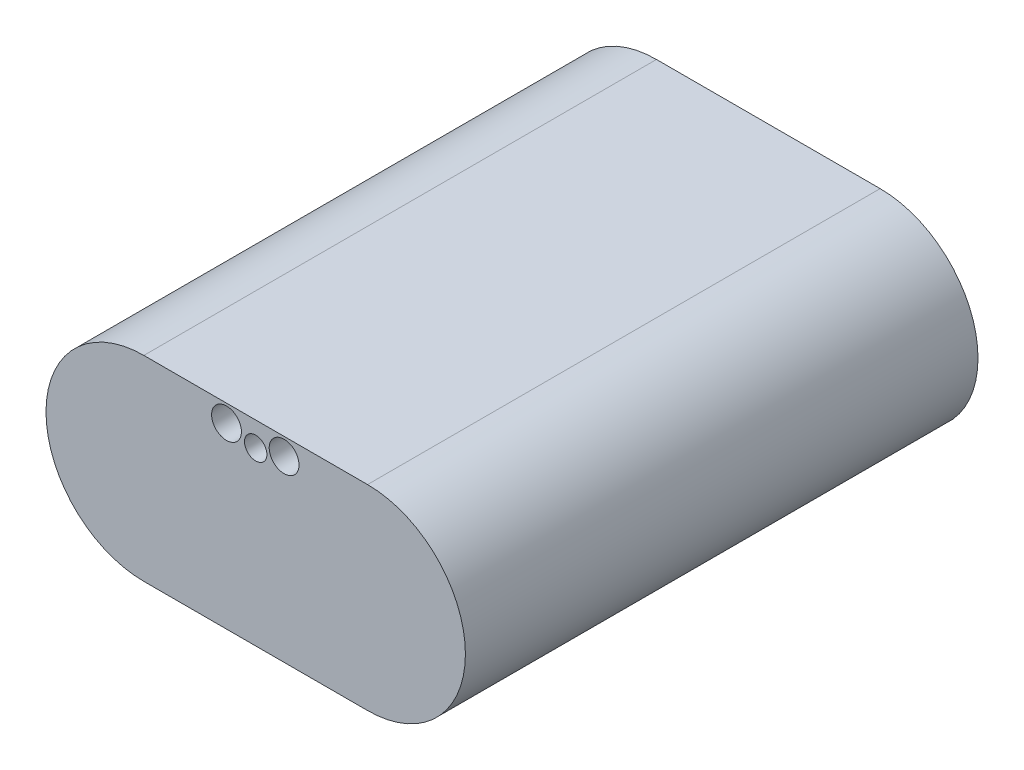
SolidWorks part; units mm, degrees
ref_plane "Front Plane" through (0, 0, 0) normal (0, 0, 1) x (1, 0, 0)
ref_plane "Top Plane" through (0, 0, 0) normal (0, 1, 0) x (1, 0, 0)
ref_plane "Right Plane" through (0, 0, 0) normal (1, 0, 0) x (0, 0, -1)
sketch "Sketch1" plane through (0, 0, 0) normal (0, 0, 1) x (1, 0, 0)
  line L0 (-60, 52.5) -> (60, 52.5)
  line L1 (-125, 125) -> (125, 125) construction
  line L2 (-125, 125) -> (-125, -125) construction
  line L3 (-125, -125) -> (125, -125) construction
  line L4 (125, 125) -> (125, -125) construction
  line L5 (-125, 125) -> (125, -125) construction
  line L6 (-125, -125) -> (125, 125) construction
  line L7 (-60, -52.5) -> (61.9615, -52.5)
  line L8 (-60, 0) -> (60, 0) construction
  circle A0 centre (-60, 0) radius 52.5
  circle A1 centre (60, 0) radius 52.5
  circle A2 centre (0, 39.4456) radius 6
  circle A3 centre (15.2407, 43.1722) radius 8
  circle A4 centre (-15.6568, 43.1722) radius 8
  point P6 (0, 0)
  point P14 (0, 0)
  point P21 (-15.6568, 43.1722)
  point P22 (15.2407, 43.1722)
  point P23 (0, 0)
  point P24 (0, 0)
  dimension "D1" = 105
  dimension "D2" = 105
  dimension "D4" = 12
  dimension "D6" = 16
  dimension "D7" = 16
  dimension "D3" = 250
  dimension "D5" = 120
extrude "Boss-Extrude1" add sketch "Sketch1" along normal mid plane 275 contours A0 | A1 L0 A0 L7 A2 | A1 A0
